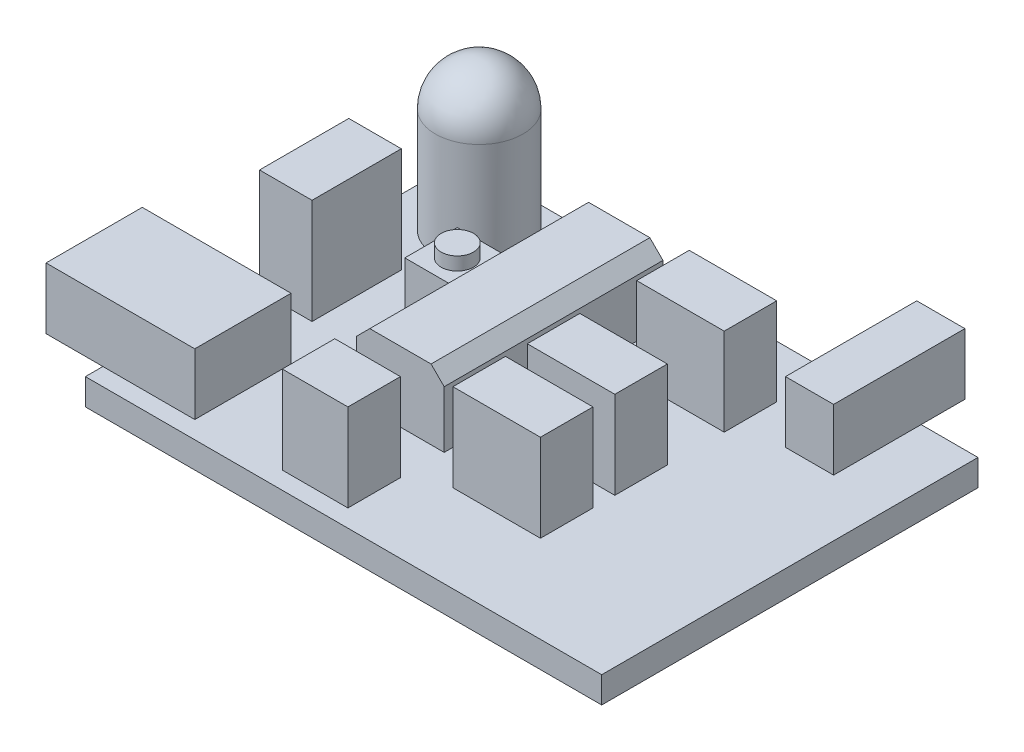
SolidWorks part; units mm, degrees
ref_plane "Front Plane" through (0, 0, 0) normal (0, 0, 1) x (1, 0, 0)
ref_plane "Top Plane" through (0, 0, 0) normal (0, 1, 0) x (1, 0, 0)
ref_plane "Right Plane" through (0, 0, 0) normal (1, 0, 0) x (0, 0, -1)
sketch "Sketch1" plane through (0, 0, 0) normal (0, 1, 0) x (1, 0, 0)
  line L1 (-29.5, -21.5) -> (29.5, -21.5)
  line L2 (-29.5, -21.5) -> (-29.5, 21.5)
  line L3 (-29.5, 21.5) -> (29.5, 21.5)
  line L4 (29.5, -21.5) -> (29.5, 21.5)
  line L5 (-29.5, -21.5) -> (29.5, 21.5) construction
  line L6 (-29.5, 21.5) -> (29.5, -21.5) construction
  point P0 (0, 0)
  dimension "D1" = 59
  dimension "D2" = 43
extrude "Boss-Extrude1" add sketch "Sketch1" along normal blind 3
sketch "Sketch2" plane through (0, 3, 0) normal (0, 1, 0) x (1, 0, 0)
  line L0 (29.5, 21.5) -> (-29.5, 21.5) construction
  line L1 (-29.5, 21.5) -> (-29.5, -21.5) construction
  circle A0 centre (-21.5, 15.5) radius 5
  dimension "D1" = 10
  dimension "D2" = 1
  dimension "D3" = 3
extrude "Boss-Extrude2" add sketch "Sketch2" along normal blind 17
sketch "Sketch3" plane through (0, 3, 0) normal (0, 1, 0) x (1, 0, 0)
  line L0 (-29.5, 21.5) -> (-29.5, -21.5) construction
  line L1 (-19, -19.5) -> (-36, -19.5)
  line L2 (-19, -19.5) -> (-19, -8.5)
  line L3 (-19, -8.5) -> (-36, -8.5)
  line L4 (-36, -19.5) -> (-36, -8.5)
  line L5 (-29.5, -21.5) -> (29.5, -21.5) construction
  dimension "D1" = 11
  dimension "D2" = 17
  dimension "D3" = 6.5
  dimension "D4" = 2
extrude "Boss-Extrude3" add sketch "Sketch3" along normal blind 7
sketch "Sketch4" plane through (0, 3, 0) normal (0, 1, 0) x (1, 0, 0)
  line L0 (29.5, -21.5) -> (29.5, 21.5) construction
  line L1 (17.5, 11.5) -> (23, 11.5)
  line L2 (17.5, 11.5) -> (17.5, 26.5)
  line L3 (17.5, 26.5) -> (23, 26.5)
  line L4 (23, 11.5) -> (23, 26.5)
  line L5 (29.5, 21.5) -> (-29.5, 21.5) construction
  dimension "D1" = 5.5
  dimension "D2" = 6.5
  dimension "D3" = 5
  dimension "D4" = 10
extrude "Boss-Extrude4" add sketch "Sketch4" along normal blind 7
fillet "Fillet1" radius 5 1 edges at (-21.5, 20, -10.5)
sketch "Sketch5" plane through (0, 3, 0) normal (0, 1, 0) x (1, 0, 0)
  line L0 (2.5, 9.5) -> (2.5, 3) construction
  line L1 (-9, -13.5) -> (-1.5, -13.5)
  line L2 (-9, -13.5) -> (-9, -19.5)
  line L3 (-9, -19.5) -> (-1.5, -19.5)
  line L4 (-1.5, -13.5) -> (-1.5, -19.5)
  line L5 (2.5, 15.5) -> (12.5, 15.5)
  line L6 (2.5, 15.5) -> (2.5, 9.5)
  line L7 (2.5, 9.5) -> (12.5, 9.5)
  line L8 (12.5, 15.5) -> (12.5, 9.5)
  line L9 (2.5, 3) -> (12.5, 3)
  line L10 (2.5, 3) -> (2.5, -3)
  line L11 (2.5, -3) -> (12.5, -3)
  line L12 (12.5, 3) -> (12.5, -3)
  line L13 (2.5, -5.5) -> (12.5, -5.5)
  line L14 (2.5, -5.5) -> (2.5, -11.5)
  line L15 (2.5, -11.5) -> (12.5, -11.5)
  line L16 (12.5, -5.5) -> (12.5, -11.5)
  line L17 (2.5, -3) -> (2.5, -5.5) construction
  line L18 (17.5, 21.5) -> (-29.5, 21.5) construction
  line L19 (-29.5, -21.5) -> (29.5, -21.5) construction
  line L21 (17.5, 26.5) -> (17.5, 11.5) construction
  line L22 (-19, -19.5) -> (-19, -8.5) construction
  point P20 (17.5, 19)
  dimension "D1" = 10
  dimension "D2" = 7.5
  dimension "D3" = 6
  dimension "D4" = 6
  dimension "D5" = 10
  dimension "D6" = 2.5
  dimension "D7" = 5
  dimension "D8" = 10
  dimension "D9" = 2
extrude "Boss-Extrude5" add sketch "Sketch5" along normal blind 10
sketch "Sketch6" plane through (0, 3, 0) normal (0, 1, 0) x (1, 0, 0)
  line L0 (-19, -8.5) -> (-36, -8.5) construction
  line L1 (-28, -3.1) -> (-22, -3.1)
  line L2 (-28, -3.1) -> (-28, 7.1)
  line L3 (-28, 7.1) -> (-22, 7.1)
  line L4 (-22, -3.1) -> (-22, 7.1)
  line L5 (-29.5, 21.5) -> (-29.5, -8.5) construction
  circle A0 centre (-21.5, 15.5) radius 5 construction
  dimension "D2" = 3.4
  dimension "D1" = 5.4
  dimension "D3" = 1.5
  dimension "D4" = 6
extrude "Boss-Extrude6" add sketch "Sketch6" along normal blind 12
sketch "Sketch7" plane through (0, 3, 0) normal (0, 1, 0) x (1, 0, 0)
  line L0 (17.5, 21.5) -> (-29.5, 21.5) construction
  line L1 (-1.5, -8.5) -> (-11.5, -8.5)
  line L2 (-1.5, -8.5) -> (-1.5, 16.5)
  line L3 (-1.5, 16.5) -> (-11.5, 16.5)
  line L4 (-11.5, -8.5) -> (-11.5, 16.5)
  line L5 (-29.5, 21.5) -> (-29.5, -8.5) construction
  dimension "D1" = 10
  dimension "D2" = 5
  dimension "D3" = 25
  dimension "D4" = 18
extrude "Boss-Extrude7" add sketch "Sketch7" along normal blind 8
chamfer "Chamfer1" distance 1.5 angle 45 2 edges at (-1.5, 11, -4) (-11.5, 11, -4)
sketch "Sketch8" plane through (0, 3, 0) normal (0, 1, 0) x (1, 0, 0)
  line L0 (-29.5, 21.5) -> (-29.5, -8.5) construction
  line L1 (-18, 3.5) -> (-12, 3.5)
  line L2 (-18, 3.5) -> (-18, 9.5)
  line L3 (-18, 9.5) -> (-12, 9.5)
  line L4 (-12, 3.5) -> (-12, 9.5)
  line L5 (17.5, 21.5) -> (-29.5, 21.5) construction
  dimension "D1" = 6
  dimension "D2" = 11.5
  dimension "D3" = 12
extrude "Boss-Extrude8" add sketch "Sketch8" along normal blind 5
sketch "Sketch9" plane through (0, 8, 0) normal (0, 1, 0) x (1, 0, 0)
  line L0 (-18, 3.5) -> (-15, 6.5) construction
  line L1 (-15, 6.5) -> (-12, 9.5) construction
  circle A0 centre (-15, 6.5) radius 1.85
  dimension "D1" = 3.7
extrude "Boss-Extrude9" add sketch "Sketch9" along normal blind 1.5
